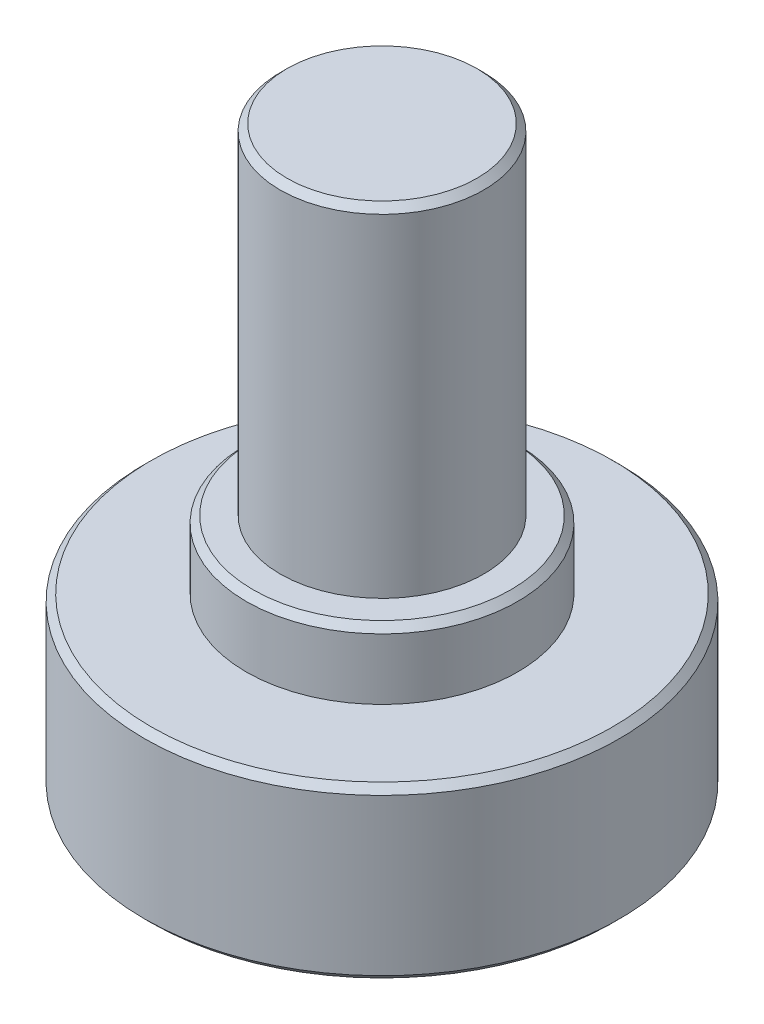
SolidWorks part; units mm, degrees
ref_plane "Front Plane" through (0, 0, 0) normal (0, 0, 1) x (1, 0, 0)
ref_plane "Top Plane" through (0, 0, 0) normal (0, 1, 0) x (1, 0, 0)
ref_plane "Right Plane" through (0, 0, 0) normal (1, 0, 0) x (0, 0, -1)
other "Configuration Table"
sketch "草图1" plane through (0, 0, 0) normal (0, 1, 0) x (1, 0, 0)
  circle A0 centre (0, 0) radius 7
extrude "凸台-拉伸1" add sketch "草图1" along normal blind 5
sketch "草图2" plane through (0, 5, 0) normal (0, 1, 0) x (1, 0, 0)
  circle A0 centre (0, 0) radius 4
extrude "凸台-拉伸2" add sketch "草图2" along normal blind 2
sketch "草图3" plane through (0, 7, 0) normal (0, 1, 0) x (1, 0, 0)
  circle A0 centre (0, 0) radius 3
  dimension "D1" = 6
extrude "凸台-拉伸3" add sketch "草图3" along normal blind 10
chamfer "倒角1" distance 0.2 angle 45 4 edges at (0, 17, 3) (0, 7, 4) (0, 0, 7) (0, 5, 7)
sketch "草图4" plane through (0, 0, 0) normal (0, -1, 0) x (1, 0, 0)
  line L1 (2.8868, 0) -> (1.4434, 2.5)
  line L2 (1.4434, 2.5) -> (-1.4434, 2.5)
  line L3 (-1.4434, 2.5) -> (-2.8868, 0)
  line L4 (-2.8868, 0) -> (-1.4434, -2.5)
  line L5 (-1.4434, -2.5) -> (1.4434, -2.5)
  line L6 (1.4434, -2.5) -> (2.8868, 0)
  circle A0 centre (0, 0) radius 2.5 construction
extrude "切除-拉伸1" cut sketch "草图4" against normal blind 2.5
